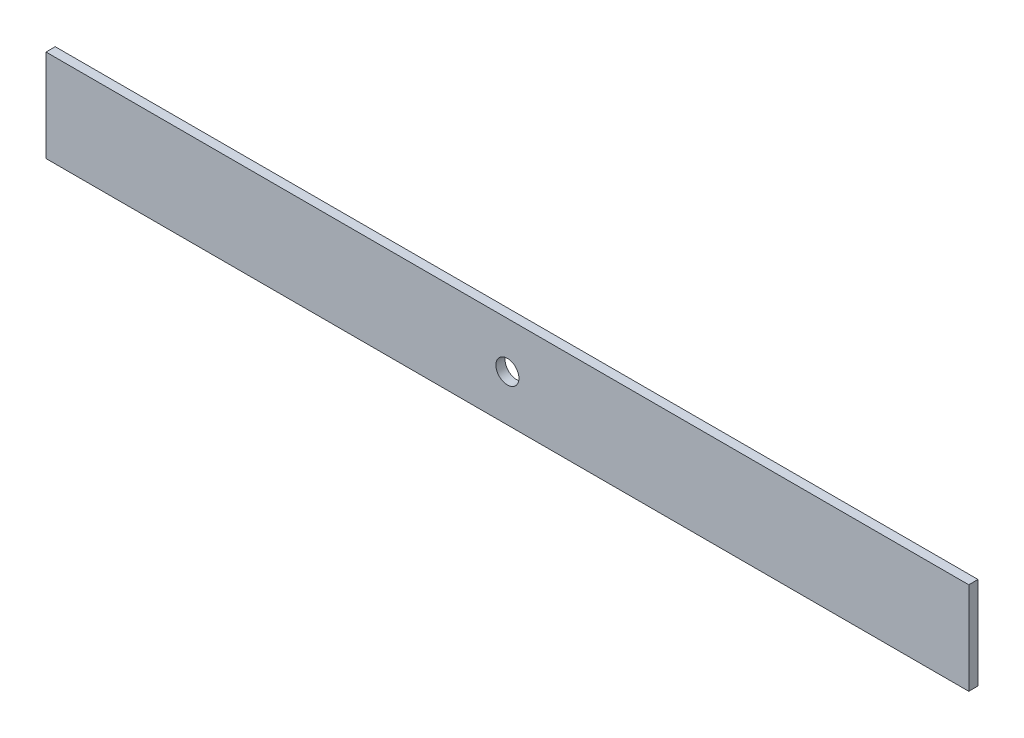
SolidWorks part; units mm, degrees
ref_plane "Front Plane" through (0, 0, 0) normal (0, 0, 1) x (1, 0, 0)
ref_plane "Top Plane" through (0, 0, 0) normal (0, 1, 0) x (1, 0, 0)
ref_plane "Right Plane" through (0, 0, 0) normal (1, 0, 0) x (0, 0, -1)
sketch "Sketch1" plane through (0, 0, 0) normal (0, 0, 1) x (1, 0, 0)
  line L1 (127, 12.7) -> (-127, 12.7)
  line L2 (127, 12.7) -> (127, -12.7)
  line L3 (127, -12.7) -> (-127, -12.7)
  line L4 (-127, 12.7) -> (-127, -12.7)
  circle A1 centre (0, 0) radius 3.175
  dimension "D1" = 254
  dimension "D3" = 6.35
  dimension "D4" = 12.7
  dimension "D2" = 127
  dimension "D5" = 12.7
extrude "Boss-Extrude1" add sketch "Sketch1" along normal blind 2.54
